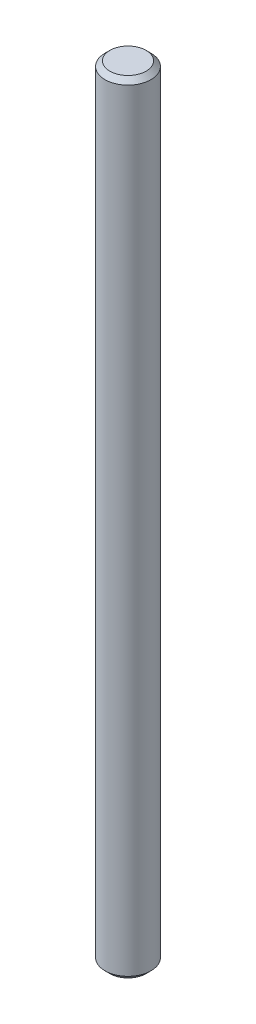
SolidWorks part; units mm, degrees
ref_plane "Front Plane" through (0, 0, 0) normal (0, 0, 1) x (1, 0, 0)
ref_plane "Top Plane" through (0, 0, 0) normal (0, 1, 0) x (1, 0, 0)
ref_plane "Right Plane" through (0, 0, 0) normal (1, 0, 0) x (0, 0, -1)
sketch "Sketch1" plane through (0, 0, 0) normal (0, 1, 0) x (1, 0, 0)
  circle A0 centre (0, 0) radius 2.35
  dimension "D1" = 4.7
extrude "Boss-Extrude1" add sketch "Sketch1" along normal blind 80
chamfer "Chamfer1" distance 0.5 angle 45 2 edges at (0, 0, 2.35) (0, 80, 2.35)
